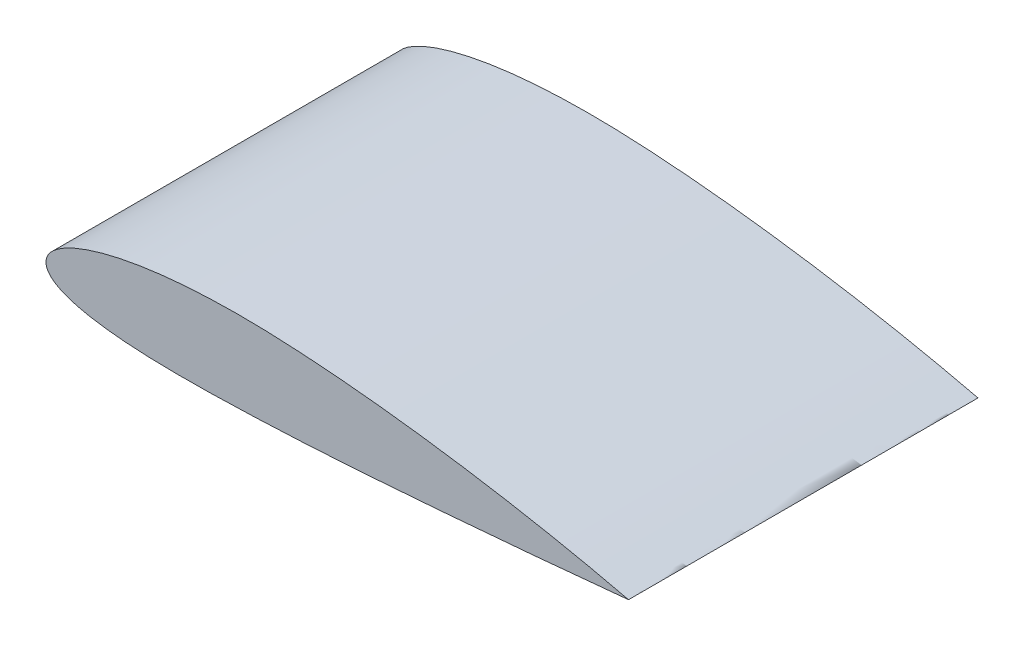
SolidWorks part; units mm, degrees
ref_plane "Front Plane" through (0, 0, 0) normal (1, 0, 0) x (0, 1, 0)
ref_plane "Top Plane" through (0, 0, 0) normal (0, 0, 1) x (0, 1, 0)
ref_plane "Right Plane" through (0, 0, 0) normal (0, 1, 0) x (-1, 0, 0)
curve "Curve1"
  spline degree 3 poles (0.9995, 0, 0) (1.0001, 0, 0) (0.9995, 0.0001, 0) (0.9989, 0.0003, 0) (0.9976, 0.0006, 0) (0.996, 0.001, 0) (0.9937, 0.0015, 0) (0.9911, 0.0021, 0) (0.9879, 0.0029, 0) (0.9843, 0.0037, 0) (0.9802, 0.0047, 0) (0.9756, 0.0057, 0) (0.9706, 0.0069, 0) (0.9651, 0.0081, 0) (0.9591, 0.0095, 0) (0.9527, 0.0109, 0) (0.9459, 0.0124, 0) (0.9386, 0.014, 0) (0.9309, 0.0157, 0) (0.9228, 0.0174, 0) (0.9142, 0.0192, 0) (0.9052, 0.0211, 0) (0.8959, 0.023, 0) (0.8861, 0.025, 0) (0.876, 0.0271, 0) (0.8655, 0.0291, 0) (0.8546, 0.0312, 0) (0.8434, 0.0334, 0) (0.8318, 0.0356, 0) (0.8199, 0.0378, 0) (0.8077, 0.04, 0) (0.7951, 0.0422, 0) (0.7823, 0.0444, 0) (0.7692, 0.0466, 0) (0.7559, 0.0489, 0) (0.7422, 0.0511, 0) (0.7283, 0.0533, 0) (0.7142, 0.0554, 0) (0.6999, 0.0576, 0) (0.6854, 0.0597, 0) (0.6707, 0.0618, 0) (0.6558, 0.0639, 0) (0.6408, 0.0659, 0) (0.6256, 0.0678, 0) (0.6102, 0.0697, 0) (0.5948, 0.0716, 0) (0.5793, 0.0734, 0) (0.5637, 0.0751, 0) (0.548, 0.0767, 0) (0.5323, 0.0783, 0) (0.5165, 0.0797, 0) (0.5007, 0.0811, 0) (0.4849, 0.0824, 0) (0.4691, 0.0836, 0) (0.4533, 0.0847, 0) (0.4376, 0.0857, 0) (0.422, 0.0866, 0) (0.4064, 0.0874, 0) (0.3908, 0.0881, 0) (0.3753, 0.0886, 0) (0.3599, 0.0889, 0) (0.3446, 0.0891, 0) (0.3295, 0.0892, 0) (0.3145, 0.0891, 0) (0.2998, 0.0888, 0) (0.2852, 0.0884, 0) (0.2709, 0.0878, 0) (0.2568, 0.0871, 0) (0.2429, 0.0862, 0) (0.2293, 0.0851, 0) (0.216, 0.0839, 0) (0.2029, 0.0826, 0) (0.1902, 0.0811, 0) (0.1778, 0.0795, 0) (0.1657, 0.0777, 0) (0.154, 0.0758, 0) (0.1426, 0.0738, 0) (0.1316, 0.0717, 0) (0.121, 0.0694, 0) (0.1108, 0.0671, 0) (0.1009, 0.0646, 0) (0.0915, 0.062, 0) (0.0825, 0.0594, 0) (0.074, 0.0567, 0) (0.0658, 0.0538, 0) (0.0581, 0.051, 0) (0.0509, 0.048, 0) (0.0441, 0.045, 0) (0.0378, 0.042, 0) (0.032, 0.0389, 0) (0.0266, 0.0357, 0) (0.0217, 0.0326, 0) (0.0173, 0.0294, 0) (0.0134, 0.0262, 0) (0.01, 0.0229, 0) (0.007, 0.0197, 0) (0.0046, 0.0164, 0) (0.0027, 0.0131, 0) (0.0012, 0.0098, 0) (0.0003, 0.0066, 0) (-0.0002, 0.0033, 0) (-0.0001, 0, 0) (0.0005, -0.0032, 0) (0.0016, -0.0064, 0) (0.0031, -0.0094, 0) (0.0052, -0.0123, 0) (0.0077, -0.0152, 0) (0.0107, -0.0179, 0) (0.0142, -0.0205, 0) (0.0181, -0.0231, 0) (0.0225, -0.0255, 0) (0.0274, -0.0278, 0) (0.0327, -0.03, 0) (0.0384, -0.0321, 0) (0.0446, -0.0341, 0) (0.0513, -0.036, 0) (0.0583, -0.0378, 0) (0.0658, -0.0395, 0) (0.0737, -0.0411, 0) (0.0819, -0.0426, 0) (0.0906, -0.0439, 0) (0.0997, -0.0452, 0) (0.1091, -0.0463, 0) (0.1189, -0.0474, 0) (0.1291, -0.0483, 0) (0.1396, -0.0491, 0) (0.1505, -0.0499, 0) (0.1617, -0.0505, 0) (0.1732, -0.051, 0) (0.185, -0.0514, 0) (0.1971, -0.0517, 0) (0.2095, -0.052, 0) (0.2221, -0.0521, 0) (0.2351, -0.0522, 0) (0.2482, -0.0521, 0) (0.2616, -0.052, 0) (0.2753, -0.0518, 0) (0.2892, -0.0515, 0) (0.3032, -0.0512, 0) (0.3175, -0.0508, 0) (0.3319, -0.0504, 0) (0.3465, -0.0499, 0) (0.3612, -0.0493, 0) (0.3761, -0.0487, 0) (0.3911, -0.0481, 0) (0.4063, -0.0474, 0) (0.4216, -0.0467, 0) (0.4371, -0.0459, 0) (0.4526, -0.045, 0) (0.4681, -0.0441, 0) (0.4837, -0.0432, 0) (0.4993, -0.0422, 0) (0.5149, -0.0412, 0) (0.5305, -0.0402, 0) (0.5461, -0.0391, 0) (0.5616, -0.038, 0) (0.5771, -0.0369, 0) (0.5925, -0.0357, 0) (0.6078, -0.0346, 0) (0.623, -0.0334, 0) (0.6381, -0.0322, 0) (0.6531, -0.0311, 0) (0.6679, -0.0299, 0) (0.6826, -0.0287, 0) (0.6971, -0.0275, 0) (0.7114, -0.0263, 0) (0.7255, -0.0251, 0) (0.7394, -0.024, 0) (0.753, -0.0228, 0) (0.7664, -0.0217, 0) (0.7796, -0.0205, 0) (0.7925, -0.0194, 0) (0.805, -0.0183, 0) (0.8173, -0.0172, 0) (0.8293, -0.0162, 0) (0.841, -0.0151, 0) (0.8523, -0.0141, 0) (0.8633, -0.0131, 0) (0.8739, -0.0121, 0) (0.8842, -0.0112, 0) (0.894, -0.0103, 0) (0.9035, -0.0094, 0) (0.9126, -0.0085, 0) (0.9213, -0.0077, 0) (0.9296, -0.0069, 0) (0.9374, -0.0062, 0) (0.9448, -0.0055, 0) (0.9518, -0.0048, 0) (0.9583, -0.0041, 0) (0.9644, -0.0036, 0) (0.97, -0.003, 0) (0.9751, -0.0025, 0) (0.9798, -0.002, 0) (0.984, -0.0016, 0) (0.9877, -0.0012, 0) (0.9909, -0.0009, 0) (0.9936, -0.0006, 0) (0.9959, -0.0004, 0) (0.9976, -0.0002, 0) (0.9989, -0.0001, 0) (0.9995, 0, 0) (1.0001, 0, 0) (0.9995, 0.0001, 0) knots -0.001099 -0.000489 -0.000122 0 0.000122 0.000489 0.001099 0.001952 0.003047 0.004385 0.005961 0.007776 0.009827 0.012113 0.01463 0.017377 0.020351 0.023548 0.026965 0.030599 0.034447 0.038504 0.042766 0.047229 0.051889 0.056741 0.06178 0.067001 0.072398 0.077968 0.083702 0.089597 0.095647 0.101844 0.108184 0.11466 0.121265 0.127994 0.134838 0.141792 0.148848 0.156 0.16324 0.170562 0.177957 0.185419 0.192941 0.200514 0.208131 0.215785 0.223468 0.231173 0.238891 0.246616 0.254339 0.262053 0.26975 0.277423 0.285064 0.292666 0.300263 0.307835 0.315346 0.322788 0.330155 0.337438 0.344633 0.35173 0.358724 0.365608 0.372376 0.379022 0.385538 0.391921 0.398162 0.404258 0.410203 0.415991 0.421617 0.427078 0.432369 0.437485 0.442422 0.447178 0.451748 0.456131 0.460322 0.464321 0.468126 0.471735 0.475149 0.478368 0.481393 0.484227 0.486873 0.489337 0.491627 0.493753 0.495728 0.497571 0.499305 0.500954 0.502554 0.504138 0.505722 0.507321 0.508971 0.510702 0.51254 0.514508 0.516623 0.518897 0.521339 0.523958 0.526757 0.529741 0.53291 0.536267 0.53981 0.54354 0.547455 0.551553 0.555832 0.56029 0.564923 0.569728 0.574702 0.579841 0.585141 0.590598 0.596207 0.601964 0.607864 0.613902 0.620073 0.626372 0.632793 0.639331 0.64598 0.652734 0.659588 0.666534 0.673568 0.680683 0.687872 0.695129 0.702447 0.709848 0.717338 0.724867 0.73243 0.740019 0.747625 0.755243 0.762864 0.770481 0.778087 0.785674 0.793234 0.800761 0.808246 0.815683 0.823064 0.830382 0.837628 0.844798 0.851882 0.858874 0.865767 0.872554 0.879229 0.885784 0.892213 0.898509 0.904667 0.910679 0.91654 0.922244 0.927784 0.933156 0.938354 0.943373 0.948206 0.95285 0.957299 0.961549 0.965595 0.969434 0.973061 0.976473 0.979664 0.982634 0.985378 0.987893 0.990176 0.992226 0.99404 0.995616 0.996953 0.998048 0.998901 0.999511 0.999878 1 1.000122 1.000489 1.001099 periodic
sketch "Sketch1" plane through (0, 0, 0) normal (0, 0, 1) x (0, 1, 0)
  spline S1 degree 3 poles (-0.005, -149.9199) (-0.0013, -150.0199) (0.0157, -149.9213) (0.04, -149.8406) (0.0846, -149.6414) (0.1446, -149.3931) (0.2228, -149.0621) (0.317, -148.6625) (0.4283, -148.1897) (0.5553, -147.6457) (0.6985, -147.0307) (0.8568, -146.3452) (1.0299, -145.5898) (1.2177, -144.7653) (1.4194, -143.8724) (1.6342, -142.9119) (1.8619, -141.8848) (2.1014, -140.792) (2.3527, -139.6345) (2.6145, -138.4133) (2.8863, -137.1296) (3.1674, -135.7847) (3.4574, -134.3798) (3.755, -132.9161) (4.0597, -131.3952) (4.3706, -129.8183) (4.6874, -128.1871) (5.0089, -126.5031) (5.3341, -124.7678) (5.6632, -122.9831) (5.9941, -121.1505) (6.327, -119.2718) (6.661, -117.3489) (6.9949, -115.3835) (7.3282, -113.3775) (7.6603, -111.333) (7.99, -109.2519) (8.3169, -107.1364) (8.64, -104.9882) (8.9589, -102.8098) (9.2724, -100.6031) (9.5801, -98.3703) (9.8811, -96.1136) (10.1746, -93.8352) (10.46, -91.5374) (10.7365, -89.2225) (11.0035, -86.8927) (11.2599, -84.5504) (11.5055, -82.198) (11.7393, -79.8378) (11.961, -77.472) (12.169, -75.1031) (12.3639, -72.7336) (12.544, -70.3656) (12.7091, -68.0017) (12.8589, -65.6443) (12.9925, -63.2958) (13.1095, -60.9542) (13.2091, -58.6188) (13.2854, -56.292) (13.3391, -53.9804) (13.3695, -51.6895) (13.3766, -49.4217) (13.3601, -47.1793) (13.3199, -44.965) (13.2564, -42.7809) (13.1693, -40.6295) (13.0586, -38.5129) (12.9251, -36.4336) (12.7685, -34.3937) (12.5898, -32.3954) (12.3887, -30.441) (12.1663, -28.5323) (11.9229, -26.6714) (11.6589, -24.8603) (11.3755, -23.101) (11.0732, -21.3952) (10.7526, -19.7448) (10.4148, -18.1513) (10.0607, -16.6165) (9.6909, -15.1419) (9.3067, -13.7289) (8.9091, -12.379) (8.4985, -11.0937) (8.0769, -9.8737) (7.6444, -8.7207) (7.2028, -7.6354) (6.7522, -6.6192) (6.2942, -5.6726) (5.8298, -4.7964) (5.3594, -3.9917) (4.8843, -3.2589) (4.4052, -2.5986) (3.9226, -2.0112) (3.4374, -1.4973) (2.9499, -1.057) (2.4605, -0.6907) (1.9696, -0.3988) (1.4771, -0.1824) (0.9838, -0.0409) (0.4899, 0.0239) (-0.0012, 0.0123) (-0.485, -0.0735) (-0.9561, -0.2347) (-1.412, -0.4695) (-1.8521, -0.7774) (-2.2767, -1.1572) (-2.6858, -1.6079) (-3.0797, -2.129) (-3.4583, -2.7199) (-3.8216, -3.38) (-4.1696, -4.1084) (-4.5021, -4.9044) (-4.8193, -5.7672) (-5.1203, -6.696) (-5.4059, -7.6896) (-5.6754, -8.7471) (-5.9287, -9.8675) (-6.1659, -11.0494) (-6.387, -12.2917) (-6.5918, -13.5933) (-6.78, -14.9528) (-6.9522, -16.3688) (-7.1082, -17.8401) (-7.2482, -19.3651) (-7.3721, -20.9424) (-7.4804, -22.5705) (-7.573, -24.248) (-7.6506, -25.9731) (-7.713, -27.7444) (-7.7613, -29.5601) (-7.7952, -31.4187) (-7.8155, -33.3185) (-7.8227, -35.2576) (-7.8172, -37.2344) (-7.7998, -39.2471) (-7.7707, -41.2938) (-7.7312, -43.3729) (-7.6814, -45.4822) (-7.6219, -47.6201) (-7.5541, -49.7844) (-7.478, -51.9734) (-7.3946, -54.185) (-7.3047, -56.4173) (-7.2087, -58.671) (-7.1084, -60.9485) (-6.9989, -63.2474) (-6.8809, -65.5625) (-6.7546, -67.8873) (-6.6211, -70.2196) (-6.4807, -72.5571) (-6.3346, -74.8976) (-6.1824, -77.2389) (-6.0258, -79.5785) (-5.8645, -81.9143) (-5.6994, -84.2441) (-5.5314, -86.5655) (-5.3601, -88.8762) (-5.187, -91.1741) (-5.0117, -93.4567) (-4.8354, -95.7221) (-4.658, -97.9678) (-4.4799, -100.1917) (-4.3021, -102.3915) (-4.1239, -104.5651) (-3.9468, -106.7103) (-3.7703, -108.8249) (-3.5947, -110.9069) (-3.421, -112.9543) (-3.2488, -114.9649) (-3.0786, -116.9367) (-2.9107, -118.8677) (-2.7453, -120.756) (-2.5828, -122.5997) (-2.4231, -124.3969) (-2.2665, -126.1458) (-2.1134, -127.8446) (-1.9639, -129.4915) (-1.8183, -131.085) (-1.6768, -132.6233) (-1.5396, -134.105) (-1.407, -135.5283) (-1.2788, -136.892) (-1.156, -138.1946) (-1.0378, -139.4347) (-0.9255, -140.611) (-0.8183, -141.7224) (-0.7174, -142.7677) (-0.6221, -143.7457) (-0.5331, -144.6555) (-0.4502, -145.4961) (-0.3741, -146.2665) (-0.3046, -146.9661) (-0.2422, -147.594) (-0.1865, -148.1496) (-0.1381, -148.6327) (-0.0968, -149.041) (-0.0631, -149.3793) (-0.0362, -149.6333) (-0.0185, -149.8367) (-0.005, -149.9199) (-0.0013, -150.0199) (0.0157, -149.9213) knots -0.001099 -0.000489 -0.000122 0 0.000122 0.000489 0.001099 0.001952 0.003047 0.004385 0.005961 0.007776 0.009827 0.012113 0.01463 0.017377 0.020351 0.023548 0.026965 0.030599 0.034447 0.038504 0.042766 0.047229 0.051889 0.056741 0.06178 0.067001 0.072398 0.077968 0.083702 0.089597 0.095647 0.101844 0.108184 0.11466 0.121265 0.127994 0.134838 0.141792 0.148848 0.156 0.16324 0.170562 0.177957 0.185419 0.192941 0.200514 0.208131 0.215785 0.223468 0.231173 0.238891 0.246616 0.254339 0.262053 0.26975 0.277423 0.285064 0.292666 0.300263 0.307835 0.315346 0.322788 0.330155 0.337438 0.344633 0.35173 0.358724 0.365608 0.372376 0.379022 0.385538 0.391921 0.398162 0.404258 0.410203 0.415991 0.421617 0.427078 0.432369 0.437485 0.442422 0.447178 0.451748 0.456131 0.460322 0.464321 0.468126 0.471735 0.475149 0.478368 0.481393 0.484227 0.486873 0.489337 0.491627 0.493753 0.495728 0.497571 0.499305 0.500954 0.502554 0.504138 0.505722 0.507321 0.508971 0.510702 0.51254 0.514508 0.516623 0.518897 0.521339 0.523958 0.526757 0.529741 0.53291 0.536267 0.53981 0.54354 0.547455 0.551553 0.555832 0.56029 0.564923 0.569728 0.574702 0.579841 0.585141 0.590598 0.596207 0.601964 0.607864 0.613902 0.620073 0.626372 0.632793 0.639331 0.64598 0.652734 0.659588 0.666534 0.673568 0.680683 0.687872 0.695129 0.702447 0.709848 0.717338 0.724867 0.73243 0.740019 0.747625 0.755243 0.762864 0.770481 0.778087 0.785674 0.793234 0.800761 0.808246 0.815683 0.823064 0.830382 0.837628 0.844798 0.851882 0.858874 0.865767 0.872554 0.879229 0.885784 0.892213 0.898509 0.904667 0.910679 0.91654 0.922244 0.927784 0.933156 0.938354 0.943373 0.948206 0.95285 0.957299 0.961549 0.965595 0.969434 0.973061 0.976473 0.979664 0.982634 0.985378 0.987893 0.990176 0.992226 0.99404 0.995616 0.996953 0.998048 0.998901 0.999511 0.999878 1 1.000122 1.000489 1.001099 only from (0, -150) to (0, -150)
extrude "Boss-Extrude1" add sketch "Sketch1" along normal blind 90
